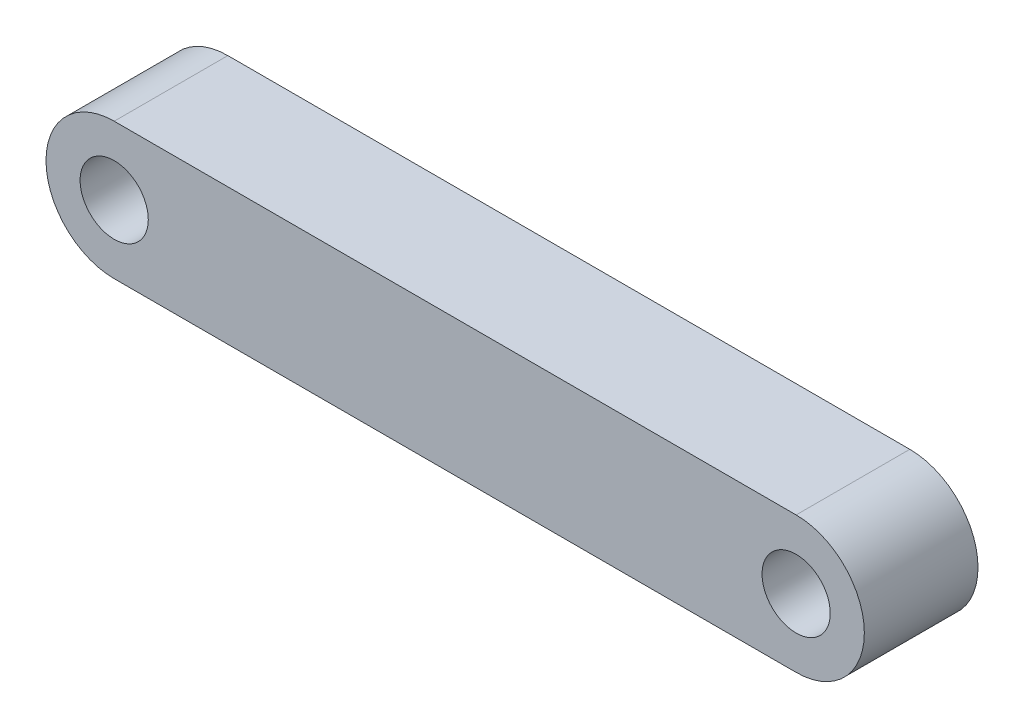
SolidWorks part; units mm, degrees
ref_plane "Plan de face" through (0, 0, 0) normal (0, 0, 1) x (1, 0, 0)
ref_plane "Plan de dessus" through (0, 0, 0) normal (0, 1, 0) x (1, 0, 0)
ref_plane "Plan de droite" through (0, 0, 0) normal (1, 0, 0) x (0, 0, -1)
sketch "Esquisse1" plane through (0, 0, 0) normal (0, 0, 1) x (1, 0, 0)
  line L0 (-15, 0) -> (15, 0) construction
  line L1 (-15, 3) -> (15, 3)
  line L2 (-15, -3) -> (15, -3)
  arc A0 (-15, 3) -> (-15, -3) centre (-15, 0) ccw
  arc A1 (15, -3) -> (15, 3) centre (15, 0) ccw
  circle A2 centre (-15, 0) radius 1.5
  circle A3 centre (15, 0) radius 1.5
  point P2 (0, 0)
  dimension "D2" = 3
  dimension "D3" = 3
  dimension "D4" = 3
  dimension "D1" = 30
extrude "Boss.-Extru.1" add sketch "Esquisse1" along normal blind 5
